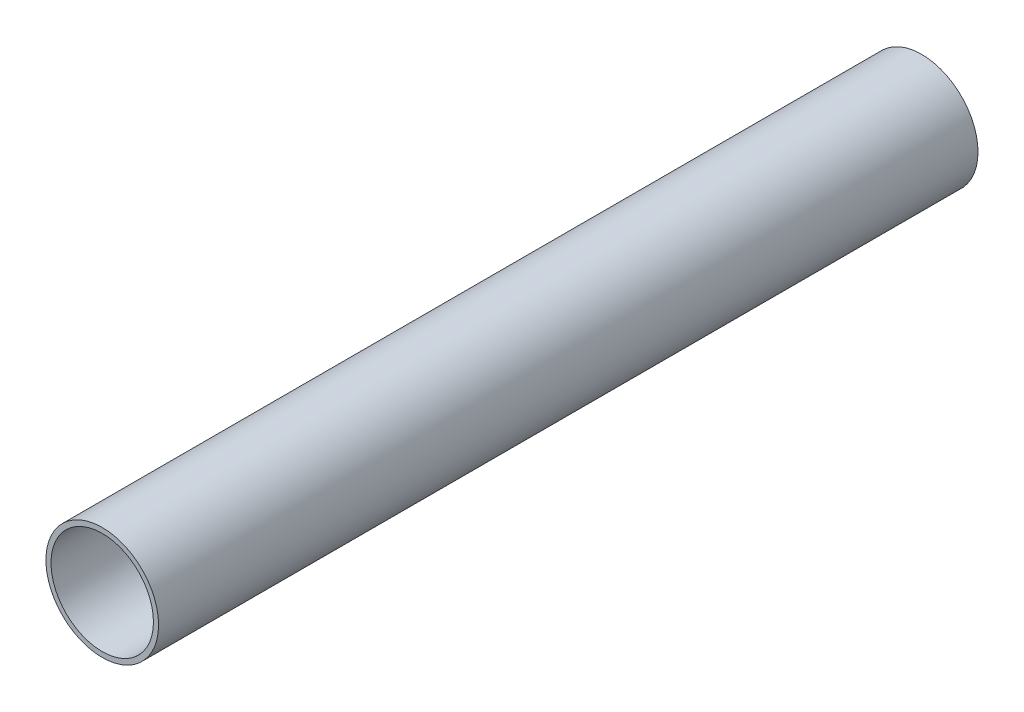
SolidWorks part; units mm, degrees
ref_plane "Front Plane" through (0, 0, 0) normal (0, 0, 1) x (1, 0, 0)
ref_plane "Top Plane" through (0, 0, 0) normal (0, 1, 0) x (1, 0, 0)
ref_plane "Right Plane" through (0, 0, 0) normal (1, 0, 0) x (0, 0, -1)
sketch "Sketch2" plane through (0, 0, 0) normal (0, 0, 1) x (1, 0, 0)
  circle A0 centre (0, 0) radius 5.5
  circle A1 centre (0, 0) radius 5
  dimension "D1" = 11
extrude "Boss-Extrude2" add sketch "Sketch2" along normal blind 80
